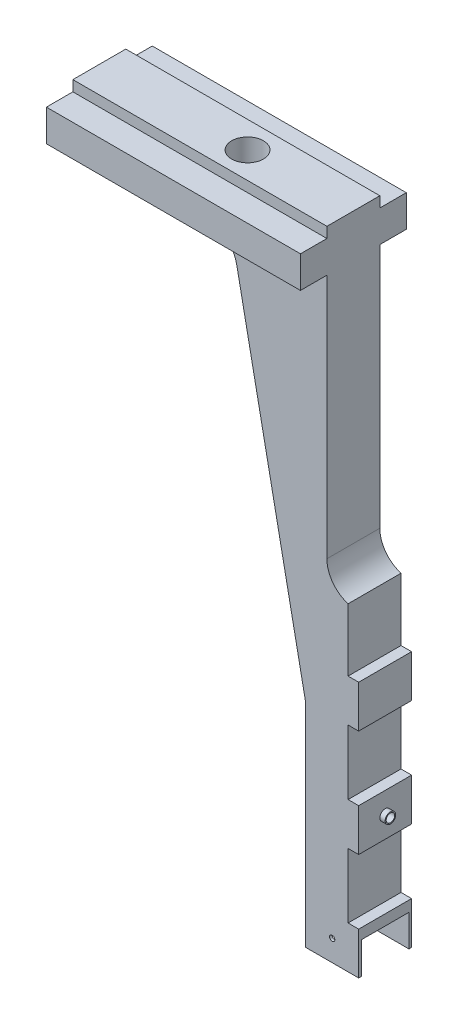
SolidWorks part; units mm, degrees
ref_plane "Front Plane" through (0, 0, 0) normal (0, 0, 1) x (1, 0, 0)
ref_plane "Top Plane" through (0, 0, 0) normal (0, 1, 0) x (1, 0, 0)
ref_plane "Right Plane" through (0, 0, 0) normal (1, 0, 0) x (0, 0, -1)
sketch "Sketch1" plane through (0, 0, 0) normal (0, 0, 1) x (1, 0, 0)
  line L0 (0, 0) -> (0, -60) construction
  line L1 (0, -60) -> (-5, -60)
  line L2 (0, -60) -> (0, -30)
  line L3 (0, -30) -> (-0.2, -30)
  line L4 (-3, -27.2) -> (-3, 0)
  line L5 (-3, 0) -> (-27, 0)
  line L6 (-27, 0) -> (-27, -5)
  line L7 (-27, -5) -> (-12, -5)
  line L8 (-12, -5) -> (-5, -40)
  line L9 (-5, -40) -> (-5, -60)
  line L10 (0, 0) -> (-3, 0) construction
  arc A0 (-0.2, -30) -> (-3, -27.2) centre (-0.2, -27.2) cw
  point P16 (-3, -30)
  dimension "D6" = 2.8
  dimension "D1" = 60
  dimension "D2" = 30
  dimension "D3" = 5
  dimension "D4" = 3
  dimension "D5" = 24
  dimension "D7" = 5
  dimension "D8" = 15
  dimension "D9" = 20
extrude "Boss-Extrude1" add sketch "Sketch1" along normal blind 5
fillet "Fillet1" radius 3 2 edges at (-5, -40, 2.5) (-12, -5, 2.5)
sketch "Sketch2" plane through (0, 0, 5) normal (0, 0, 1) x (1, 0, 0)
  line L0 (-27, 0) -> (-27, -5) construction
  line L1 (-27, -1) -> (-3, -1)
  line L2 (-27, -1) -> (-27, -4)
  line L3 (-27, -4) -> (-3, -4)
  line L4 (-3, -1) -> (-3, -4)
  line L5 (-3, -27.2) -> (-3, 0) construction
  line L6 (-27, -5) -> (-14.4594, -5) construction
  line L7 (-3, 0) -> (-27, 0) construction
  dimension "D1" = 1
  dimension "D2" = 1
extrude "Boss-Extrude2" add sketch "Sketch2" along normal blind 2.5
sketch "Sketch3" plane through (0, 0, 0) normal (0, 0, -1) x (-1, 0, 0)
  line L0 (27, 0) -> (27, -5) construction
  line L1 (3, -4) -> (27, -4)
  line L2 (3, -4) -> (3, -1)
  line L3 (3, -1) -> (27, -1)
  line L4 (27, -4) -> (27, -1)
  line L5 (3, 0) -> (27, 0) construction
  line L6 (27, -5) -> (14.4594, -5) construction
  dimension "D1" = 1
  dimension "D2" = 1
extrude "Boss-Extrude3" add sketch "Sketch3" along normal blind 2.5
sketch "Sketch4" plane through (0, 0, 0) normal (1, 0, 0) x (0, 0, -1)
  line L0 (-5, -60) -> (-5, -30) construction
  line L1 (-5, -56) -> (0, -56)
  line L2 (-5, -56) -> (-5, -49.9)
  line L3 (-5, -49.9) -> (0, -49.9)
  line L4 (0, -56) -> (0, -49.9)
  line L5 (0, -60) -> (0, -30) construction
  line L6 (-5, -60) -> (0, -60) construction
  line L7 (-5, -39.8) -> (0, -39.8)
  line L8 (-5, -45.9) -> (0, -45.9)
  line L9 (0, -45.9) -> (0, -39.8)
  line L10 (-5, -45.9) -> (-5, -39.8)
  line L11 (-5, -29.7) -> (0, -29.7)
  line L12 (-5, -35.8) -> (0, -35.8)
  line L13 (0, -35.8) -> (0, -29.7)
  line L14 (-5, -35.8) -> (-5, -29.7)
  line L15 (-5, -19.6) -> (0, -19.6)
  line L16 (-5, -25.7) -> (0, -25.7)
  line L17 (0, -25.7) -> (0, -19.6)
  line L18 (-5, -25.7) -> (-5, -19.6)
  line L19 (-5, -9.5) -> (0, -9.5)
  line L20 (-5, -15.6) -> (0, -15.6)
  line L21 (0, -15.6) -> (0, -9.5)
  line L22 (-5, -15.6) -> (-5, -9.5)
  line L23 (-5, 0.6) -> (0, 0.6)
  line L24 (-5, -5.5) -> (0, -5.5)
  line L25 (0, -5.5) -> (0, 0.6)
  line L26 (-5, -5.5) -> (-5, 0.6)
  dimension "D1" = 4
  dimension "D2" = 6.1
  dimension "D3" = 6
extrude "Cut-Extrude1" cut sketch "Sketch4" against normal blind 1
sketch "Sketch5" plane through (0, 0, 0) normal (0, 1, 0) x (1, 0, 0)
  line L0 (-27, -2.5) -> (0, -2.5) construction
  line L1 (-27, -5) -> (-27, 0) construction
  line L2 (0, -5) -> (0, 0) construction
  circle A0 centre (-13, -2.5) radius 1.5
  dimension "D1" = 3
  dimension "D2" = 14
extrude "Cut-Extrude2" cut sketch "Sketch5" against normal blind 14
ref_plane "Plane1" through (0, 0, 2.5) normal (0, 0, 1) x (1, 0, 0)
sketch "Sketch6" plane through (0, 0, 2.5) normal (0, 0, 1) x (1, 0, 0)
  line L0 (-13, 0) -> (-13, -6.7224) construction
  line L1 (-11.5, 0) -> (-14.5, 0) construction
sketch "Sketch7" plane through (0, 0, 5) normal (0, 0, 1) x (1, 0, 0)
  circle A0 centre (-2.5, -58) radius 0.25
  dimension "D1" = 0.5
extrude "Cut-Extrude3" cut sketch "Sketch7" against normal blind 10
sketch "Sketch8" plane through (0, 0, 0) normal (1, 0, 0) x (0, 0, -1)
  line L0 (-0.25, -60) -> (-0.25, -57)
  line L1 (-5, -60) -> (0, -60) construction
  line L2 (-0.25, -57) -> (-4.75, -57)
  line L3 (-4.75, -57) -> (-4.75, -60)
  line L4 (-4.75, -60) -> (-0.25, -60)
  dimension "D1" = 0.25
  dimension "D2" = 0.25
  dimension "D3" = 3
  dimension "D4" = 4.5
extrude "Cut-Extrude4" cut sketch "Sketch8" against normal blind 5
sketch "Sketch12" plane through (0, 0, 0) normal (1, 0, 0) x (0, 0, -1)
  line L0 (-5, -45.9) -> (0, -49.9) construction
  line L1 (0, -45.9) -> (-5, -49.9) construction
  circle A0 centre (-2.5, -47.9) radius 0.5
  dimension "D1" = 1
extrude "Boss-Extrude4" add sketch "Sketch12" along normal blind 0.5
sketch "Sketch13" plane through (0.5, 0, 0) normal (1, 0, 0) x (0, 0, -1)
  circle A0 centre (-2.5, -47.9) radius 0.4
  dimension "D1" = 0.8
extrude "Cut-Extrude5" cut sketch "Sketch13" against normal blind 3.5
